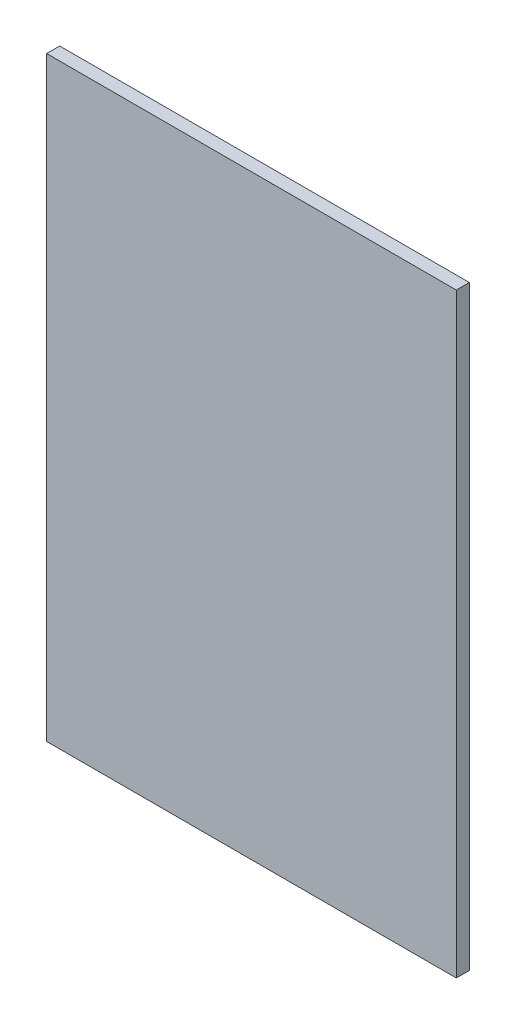
SolidWorks part; units mm, degrees
material "Glass"
ref_plane "Front Plane" through (0, 0, 0) normal (0, 0, 1) x (1, 0, 0)
ref_plane "Top Plane" through (0, 0, 0) normal (0, 1, 0) x (1, 0, 0)
ref_plane "Right Plane" through (0, 0, 0) normal (1, 0, 0) x (0, 0, -1)
sketch "Sketch1" plane through (0, 0, 0) normal (0, 0, 1) x (1, 0, 0)
  line L1 (0, 0) -> (558.8, 0)
  line L2 (0, 0) -> (0, 812.8)
  line L3 (0, 812.8) -> (558.8, 812.8)
  line L4 (558.8, 0) -> (558.8, 812.8)
  dimension "D1" = 812.8
  dimension "D2" = 558.8
extrude "Boss-Extrude1" add sketch "Sketch1" along normal blind 17.78
